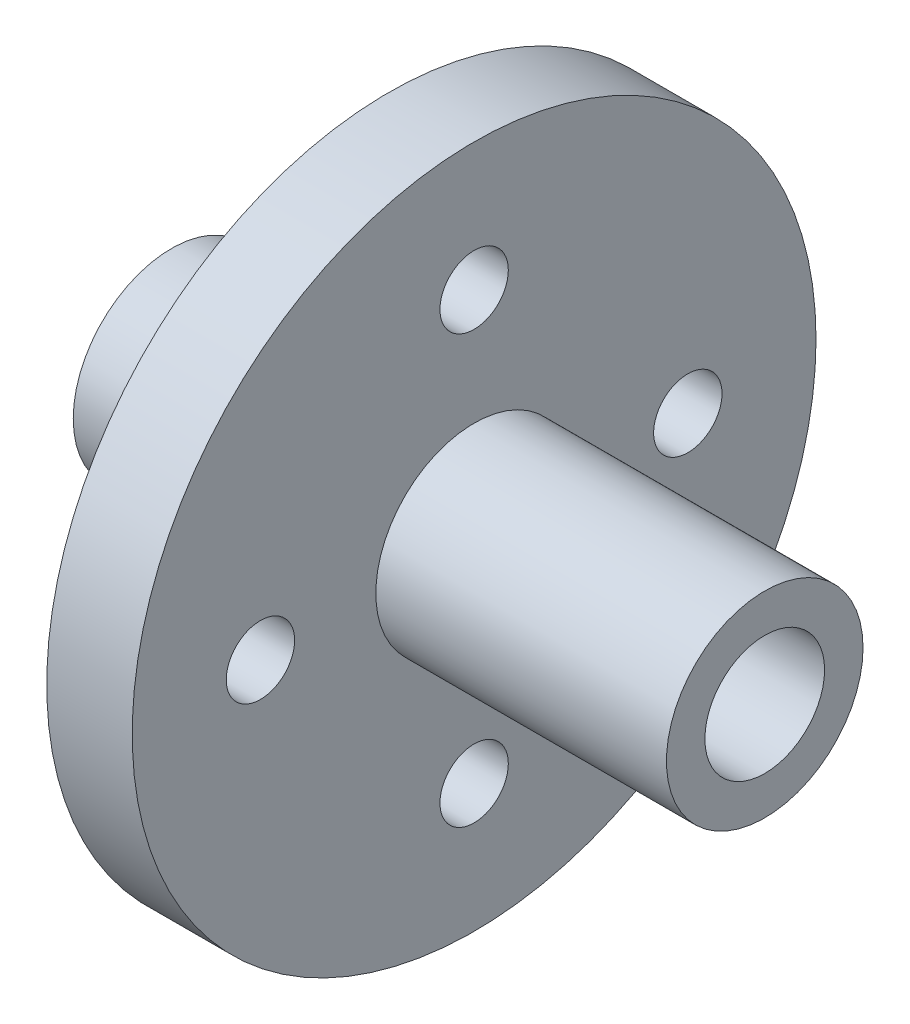
SolidWorks part; units mm, degrees
material "ABS"
ref_plane "Front Plane" through (0, 0, 0) normal (0, 0, 1) x (1, 0, 0)
ref_plane "Top Plane" through (0, 0, 0) normal (0, 1, 0) x (1, 0, 0)
ref_plane "Right Plane" through (0, 0, 0) normal (1, 0, 0) x (0, 0, -1)
sketch "Sketch1" plane through (0, 0, 0) normal (1, 0, 0) x (0, 0, -1)
  circle A0 centre (0, 0) radius 20
  circle A1 centre (0, 0) radius 3.5
  dimension "D1" = 40
  dimension "D2" = 7
extrude "Boss-Extrude1" add sketch "Sketch1" along normal blind 5
sketch "Sketch3" plane through (0, 0, 0) normal (-1, 0, 0) x (0, 0, 1)
  circle A0 centre (0, 0) radius 3.5 construction
  circle A1 centre (0, 0) radius 5.75
  circle A2 centre (0, 0) radius 3.5
  dimension "D1" = 11.5
extrude "Boss-Extrude2" add sketch "Sketch3" along normal blind 12.7 and the other way offset from surface (22 mm away) 17 other way up to face at (5, 0, -20)
hole_wizard "Ø4.0 (4) Diameter Hole1" positions "Sketch5" profile "Sketch4" hole size "Ø4.0" standard "ISO"
sketch "Sketch5" plane through (5, 0, 0) normal (1, 0, 0) x (0, 0, -1)
  point P0 (12.5, 0)
  point P2 (0, -12.5)
  point P4 (-12.5, 0)
  point P6 (0, 12.5)
  dimension "D1" = 25
  dimension "D2" = 25
  dimension "D3" = 12.5
  dimension "D4" = 12.5
sketch "Sketch4" plane through (5, 0, -12.5) normal (0, 1, 0) x (0, 0, -1)
  line L0 (0, 0) -> (0, 16.2017)
  line L1 (0, 16.2017) -> (2, 15)
  line L2 (2, 15) -> (2, 0)
  line L5 (2, 0) -> (0, 0)
  line L10 (0, 16.2017) -> (-2, 15) construction
  line L11 (0, -6.35) -> (0, 107.95) construction
  dimension "Hole Dia." = 4
  dimension "Hole Depth" = 15
  dimension "Drill Angle" = 118
